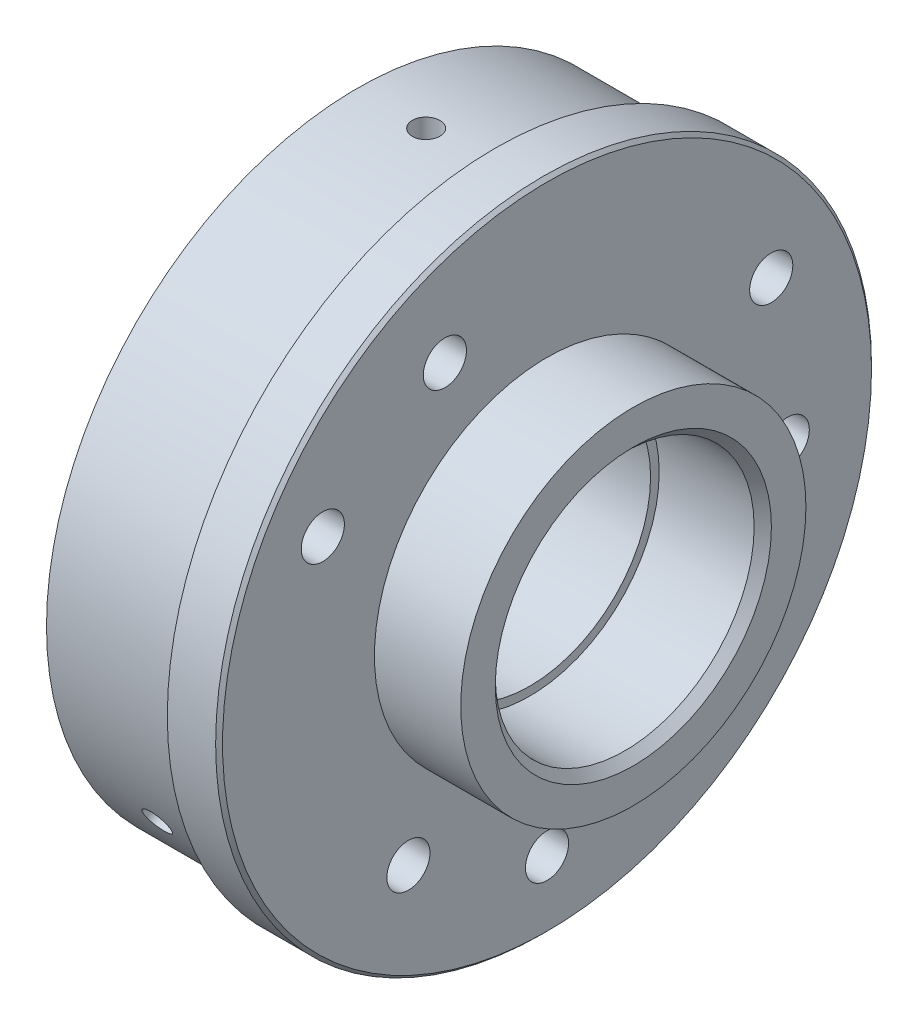
SolidWorks part; units mm, degrees
material "6061-T6 (SS)"
ref_plane "Front Plane" through (0, 0, 0) normal (0, 0, 1) x (1, 0, 0)
ref_plane "Top Plane" through (0, 0, 0) normal (0, 1, 0) x (1, 0, 0)
ref_plane "Right Plane" through (0, 0, 0) normal (1, 0, 0) x (0, 0, -1)
sketch "BaseS" plane through (0, 0, 0) normal (1, 0, 0) x (0, 0, -1)
  circle A0 centre (0, 0) radius 19
  dimension "Dia" = 38
extrude "Base" add sketch "BaseS" along normal blind 3
sketch "WallS" plane through (3, 0, 0) normal (1, 0, 0) x (0, 0, -1)
  circle A0 centre (0, 0) radius 10
  circle A1 centre (0, 0) radius 7.5
  dimension "OuterDia" = 20
  dimension "RefInnerDia" = 15
  dimension "Thickness" = 2.5
extrude "Wall" add sketch "WallS" along normal blind 5
sketch "FasteningBodyS" plane through (0, 0, 0) normal (-1, 0, 0) x (0, 0, 1)
  circle A0 centre (0, 0) radius 18
  circle A1 centre (0, 0) radius 19 construction
  dimension "DiaControl" = 1
extrude "FasteningBody" add sketch "FasteningBodyS" along normal blind 8
ref_plane "FasteningBodyP" through (0, 18, 0) normal (0, 1, 0) x (1, 0, 0)
hole_wizard "M2x0.4 Tapped Hole1" positions "Sketch4" profile "Sketch5" tap size "M2x0.4" standard "ANSI Metric"
sketch "Sketch4" plane through (0, 18, 0) normal (0, 1, 0) x (1, 0, 0)
  line L0 (0, 0) -> (-4, 0) construction
  point P0 (-4, 0)
  dimension "XDim" = 4
sketch "Sketch5" plane through (-4, 18, 0) normal (1, 0, 0) x (0, 0, 1)
  line L0 (0, 0) -> (0, 5.6807)
  line L1 (0, 5.6807) -> (0.8, 5.2)
  line L2 (0.8, 5.2) -> (0.8, 0)
  line L5 (0.8, 0) -> (0, 0)
  line L10 (0, 5.6807) -> (-0.8, 5.2) construction
  line L11 (0, -6.35) -> (0, 107.95) construction
  dimension "Tap Drill Dia." = 1.6
  dimension "Tap Drill Depth" = 5.2
  dimension "Drill Angle" = 118
cosmetic thread "Hole Thread1" parameters "D1"=4, "D2"=2
pattern_circular "CirPattern1" count 3 over 360 about axis through (-8, 0, 0) along (1, 0, 0) of "M2x0.4 Tapped Hole1"
sketch "BearingAccessBoreS" plane through (3, 0, 0) normal (1, 0, 0) x (0, 0, -1)
  circle A0 centre (0, 0) radius 7
  dimension "Dia" = 14
extrude "BearingAccessBore" cut sketch "BearingAccessBoreS" against normal through all
sketch "AdditionalDepthCutS" plane through (3, 0, 0) normal (1, 0, 0) x (0, 0, -1)
  circle A1 centre (0, 0) radius 7.5
  circle A2 centre (0, 0) radius 7.5
  dimension "D1" = 0
extrude "AdditionalDepthCut" cut sketch "AdditionalDepthCutS" against normal blind 1
hole_wizard "M3x0.5 Tapped Hole2" positions "Sketch10" profile "Sketch11" tap size "M3x0.5" standard "ANSI Metric"
sketch "Sketch10" plane through (3, 0, 0) normal (1, 0, 0) x (0, 0, -1)
  line L3 (0, 0) -> (0, -15) construction
  circle A0 centre (0, 0) radius 15 construction
  point P0 (0, -15)
  dimension "BodyCenterDia" = 30
sketch "Sketch11" plane through (3, -15, 0) normal (0, 1, 0) x (0, 0, -1)
  line L0 (0, 0) -> (0, 8.2511)
  line L1 (0, 8.2511) -> (1.25, 7.5)
  line L2 (1.25, 7.5) -> (1.25, 0)
  line L5 (1.25, 0) -> (0, 0)
  line L10 (0, 8.2511) -> (-1.25, 7.5) construction
  line L11 (0, -6.35) -> (0, 107.95) construction
  dimension "Tap Drill Dia." = 2.5
  dimension "Tap Drill Depth" = 7.5
  dimension "Drill Angle" = 118
cosmetic thread "Hole Thread3" parameters "D1"=6, "D2"=3
hole_wizard "M3x0.5 Tapped Hole1" positions "Sketch7" profile "Sketch8" tap size "M3x0.5" standard "ANSI Metric"
sketch "Sketch7" plane through (3, 0, 0) normal (1, 0, 0) x (0, 0, -1)
  line L1 (0, 0) -> (-8.0301, -11.4681) construction
  line L3 (0, 8.8) -> (0, -8.8) construction
  circle A0 centre (0, 0) radius 14 construction
  point P0 (-8.0301, -11.4681)
  dimension "BodyCenterDia" = 28
  dimension "Angle" = 35
sketch "Sketch8" plane through (3, -11.4681, 8.0301) normal (0, 1, 0) x (0, 0, -1)
  line L0 (0, 0) -> (0, 8.2511)
  line L1 (0, 8.2511) -> (1.25, 7.5)
  line L2 (1.25, 7.5) -> (1.25, 0)
  line L5 (1.25, 0) -> (0, 0)
  line L10 (0, 8.2511) -> (-1.25, 7.5) construction
  line L11 (0, -6.35) -> (0, 107.95) construction
  dimension "Tap Drill Dia." = 2.5
  dimension "Tap Drill Depth" = 7.5
  dimension "Drill Angle" = 118
cosmetic thread "Hole Thread2" parameters "D1"=6, "D2"=3
pattern_circular "CirPattern2" count 3 over 360 about axis through (0, 0, 0) along (1, 0, 0) of "M3x0.5 Tapped Hole1"
pattern_circular "CirPattern3" count 3 over 360 about axis through (0, 0, 0) along (1, 0, 0) of "M3x0.5 Tapped Hole2"
chamfer "Chamfer1" distance 0.5 1 edges at (8, 0, -7.5)
chamfer "Chamfer2" distance 0.2 1 edges at (3, 0, -19)
